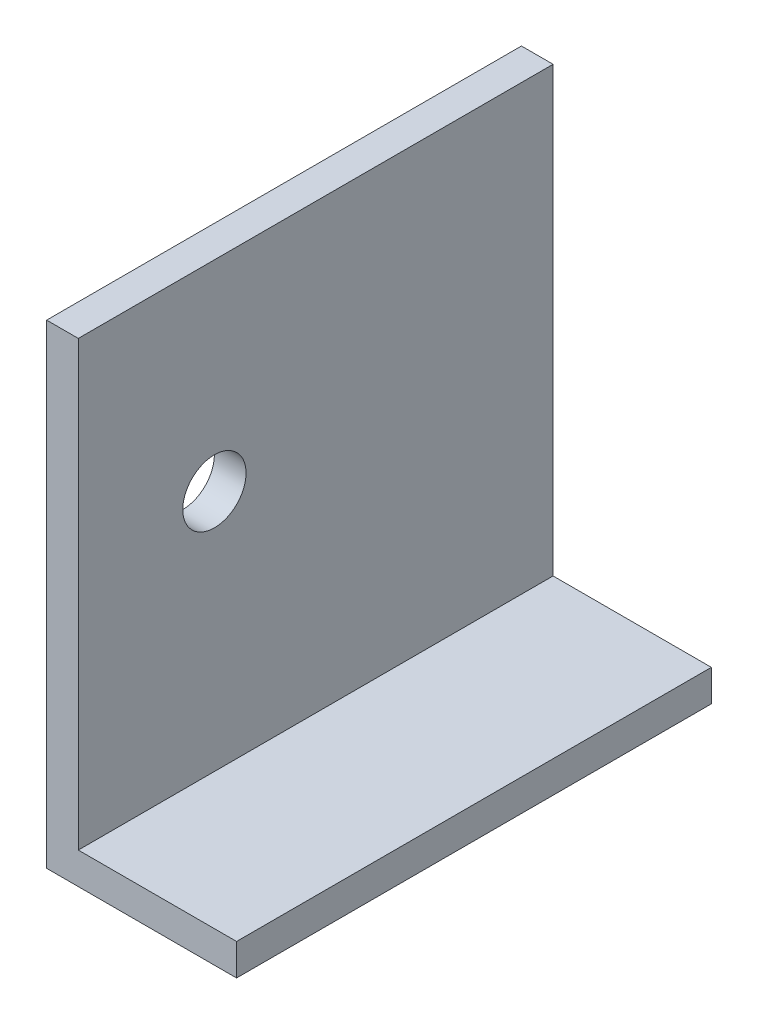
SolidWorks part; units mm, degrees
ref_plane "前视基准面" through (0, 0, 0) normal (0, 0, 1) x (1, 0, 0)
ref_plane "上视基准面" through (0, 0, 0) normal (0, 1, 0) x (1, 0, 0)
ref_plane "右视基准面" through (0, 0, 0) normal (1, 0, 0) x (0, 0, -1)
other "Configuration Table"
sketch "草图1" plane through (0, 0, 0) normal (0, 0, 1) x (1, 0, 0)
  line L1 (0, 45) -> (3, 45)
  line L2 (0, 45) -> (0, 0)
  line L3 (0, 0) -> (3, 0)
  line L4 (3, 45) -> (3, 0)
  line L5 (3, 3) -> (18, 3)
  line L6 (3, 3) -> (3, 0)
  line L7 (3, 0) -> (18, 0)
  line L8 (18, 3) -> (18, 0)
  dimension "D1" = 3
  dimension "D2" = 45
  dimension "D3" = 15
  dimension "D4" = 3
extrude "凸台-拉伸1" add sketch "草图1" along normal blind 45 contours L4 L1 L2 L3 | L6 L5 L8 L7
sketch "草图2" plane through (3, 0, 0) normal (1, 0, 0) x (0, 0, -1)
  line L0 (-45, 45) -> (-45, 3) construction
  line L2 (-45, 45) -> (0, 45) construction
  circle A0 centre (-32.1, 26) radius 3
  dimension "D1" = 6
  dimension "D2" = 12.9
  dimension "D3" = 19
extrude "切除-拉伸1" cut sketch "草图2" against normal blind 64.5
